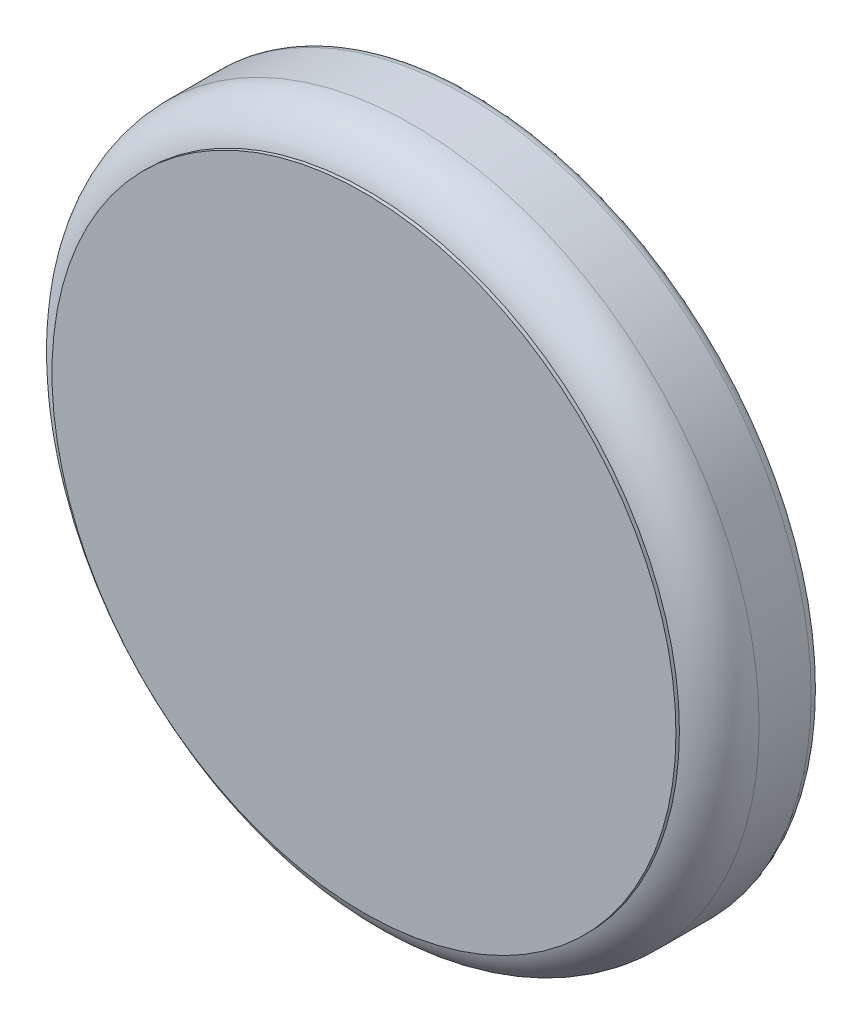
SolidWorks part; units mm, degrees
ref_plane "Front Plane" through (0, 0, 0) normal (0, 0, 1) x (1, 0, 0)
ref_plane "Top Plane" through (0, 0, 0) normal (0, 1, 0) x (1, 0, 0)
ref_plane "Right Plane" through (0, 0, 0) normal (1, 0, 0) x (0, 0, -1)
sketch "Sketch1" plane through (0, 0, 0) normal (0, 1, 0) x (1, 0, 0)
  line L0 (0, 0) -> (0, 3.2)
  line L1 (0, 3.2) -> (9.7, 3.2)
  line L2 (10, 2.9) -> (10, 1.4)
  line L3 (0, 0) -> (9, 0)
  line L4 (9, 0) -> (9, 0.1)
  arc A0 (9, 0.1) -> (10, 1.4) centre (8.655, 1.4) ccw
  arc A1 (9.7, 3.2) -> (10, 2.9) centre (9.7, 2.9) cw
  dimension "D6" = 0.3
  dimension "D1" = 10
  dimension "D2" = 3.2
  dimension "D3" = 0.1
  dimension "D4" = 9
  dimension "D5" = 1.4
revolve "Revolve1" add sketch "Sketch1" angle 360 about L0
